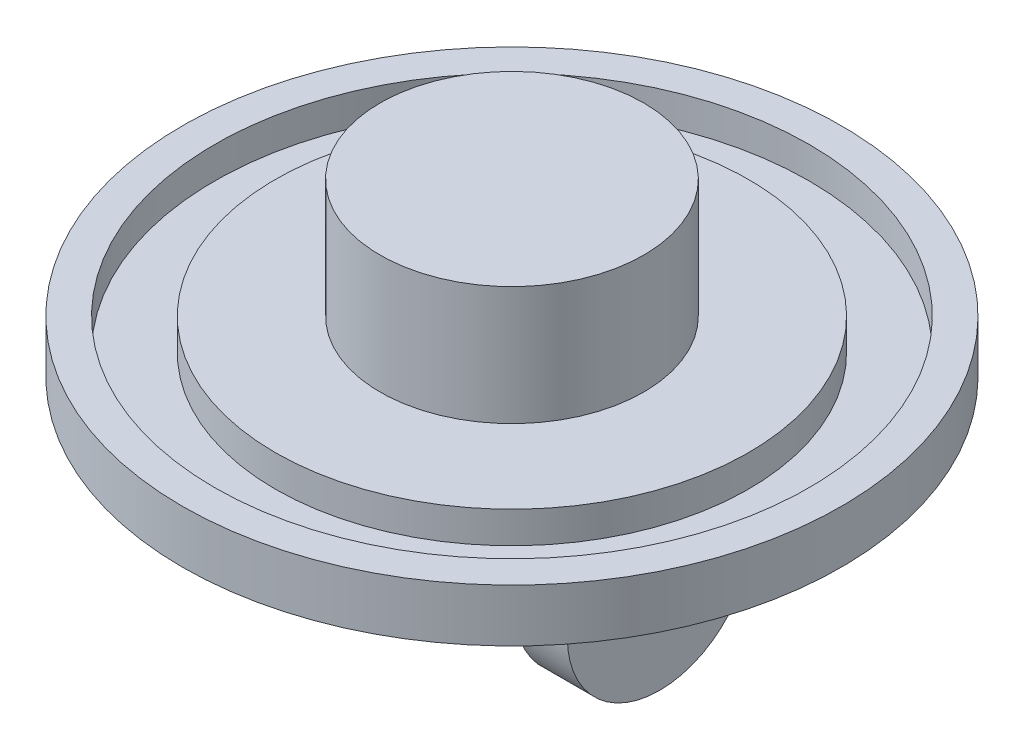
SolidWorks part; units mm, degrees
ref_plane "Ebene vorne" through (0, 0, 0) normal (0, 0, 1) x (1, 0, 0)
ref_plane "Ebene oben" through (0, 0, 0) normal (0, 1, 0) x (1, 0, 0)
ref_plane "Ebene rechts" through (0, 0, 0) normal (1, 0, 0) x (0, 0, -1)
sketch "Skizze1" plane through (0, 0, 0) normal (0, 1, 0) x (1, 0, 0)
  circle A0 centre (0, 0) radius 125
extrude "Aufsatz-Linear austragen1" add sketch "Skizze1" along normal blind 20
sketch "Skizze2" plane through (0, 20, 0) normal (0, 1, 0) x (1, 0, 0)
  circle A0 centre (0, 0) radius 50
extrude "Aufsatz-Linear austragen2" add sketch "Skizze2" along normal blind 45
sketch "Skizze3" plane through (0, 0, 0) normal (0, -1, 0) x (1, 0, 0)
  line L0 (0, 0) -> (0, 15.8821) construction
  line L1 (-36, -35) -> (36, -35)
  line L2 (-36, -35) -> (-36, 35)
  line L3 (-36, 35) -> (36, 35)
  line L4 (36, -35) -> (36, 35)
  line L5 (-36, -35) -> (36, 35) construction
  line L6 (-36, 35) -> (36, -35) construction
  line L7 (-36, 35) -> (-56, 35)
  line L8 (-36, 35) -> (-36, -35)
  line L9 (-36, -35) -> (-56, -35)
  line L10 (-56, 35) -> (-56, -35)
  line L11 (36, -35) -> (56, -35)
  line L12 (56, 35) -> (56, -35)
  line L13 (36, 35) -> (56, 35)
  line L14 (36, 35) -> (36, -35)
  point P0 (0, 0)
  dimension "D1" = 72
  dimension "D2" = 70
  dimension "D3" = 20
extrude "Aufsatz-Linear austragen3" add sketch "Skizze3" along normal blind 75 contours L7 L10 L9 L2 | L13 L4 L11 L12
sketch "Skizze4" plane through (-56, 0, 0) normal (-1, 0, 0) x (0, 0, 1)
  line L0 (-35, -40) -> (-35, -75)
  line L1 (-35, -75) -> (35, -75)
  line L2 (35, -75) -> (35, -40)
  circle A0 centre (0, -40) radius 35
  line M3 (-35, 0) -> (-35, -75)
  line M4 (-35, -75) -> (35, -75)
  line M5 (35, -75) -> (35, 0)
extrude "Schnitt-Linear austragen1" cut sketch "Skizze4" against normal up to surface (112 mm away) contours A0 M3 M4 | A0 L1 M5 up to face at (56, -37.5, 0)
sketch "Skizze5" plane through (0, 20, 0) normal (0, 1, 0) x (1, 0, 0)
  circle A0 centre (0, 0) radius 112.75
  circle A1 centre (0, 0) radius 89.75
  dimension "D1" = 179.5
  dimension "D2" = 225.5
extrude "Schnitt-Linear austragen2" cut sketch "Skizze5" against normal blind 12 contours A0 | A1
sketch "Skizze6" plane through (0, 0, 0) normal (0, -1, 0) x (1, 0, 0)
  circle A0 centre (0, 0) radius 15
extrude "Schnitt-Linear austragen3" cut sketch "Skizze6" against normal blind 6
sketch "Skizze7" plane through (0, 6, 0) normal (0, -1, 0) x (-1, 0, 0)
  circle A0 centre (0, 0) radius 6
extrude "Schnitt-Linear austragen4" cut sketch "Skizze7" against normal blind 50
